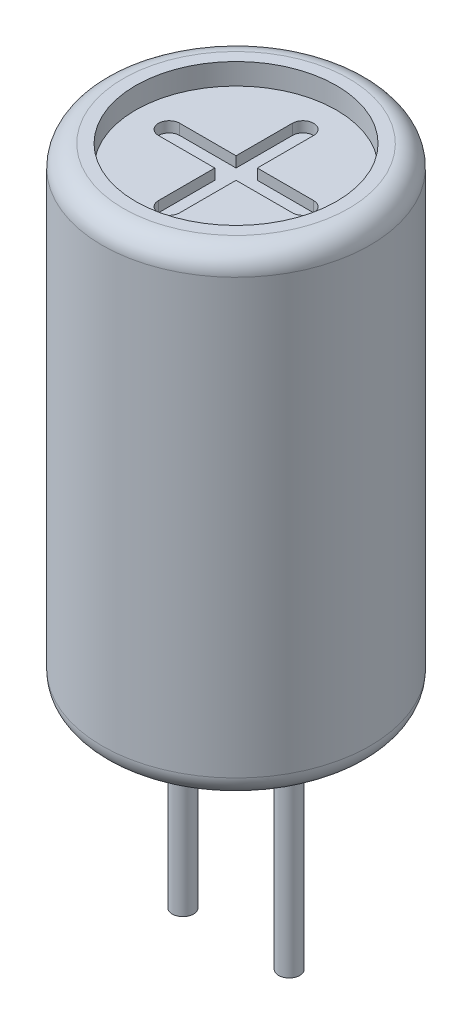
SolidWorks part; units mm, degrees
ref_plane "前视基准面" through (0, 0, 0) normal (0, 0, 1) x (1, 0, 0)
ref_plane "上视基准面" through (0, 0, 0) normal (0, 1, 0) x (1, 0, 0)
ref_plane "右视基准面" through (0, 0, 0) normal (1, 0, 0) x (0, 0, -1)
sketch "草图2" plane through (0, 0, 0) normal (0, 1, 0) x (1, 0, 0)
  circle A0 centre (0, 0) radius 3.15
  dimension "D1" = 6.3
extrude "凸台-拉伸1" add sketch "草图2" along normal blind 11.2 contours A0
fillet "圆角1" radius 0.5 2 edges at (0, 0, 3.15) (0, 11.2, 3.15)
sketch "草图3" plane through (0, 0, 0) normal (0, -1, 0) x (1, 0, 0)
  line L0 (-1.25, 0) -> (1.25, 0) construction
  circle A0 centre (-1.25, 0) radius 0.25
  circle A1 centre (1.25, 0) radius 0.25
  point P4 (0, 0)
  dimension "D2" = 0.5
  dimension "D3" = 0.5
  dimension "D1" = 2.5
extrude "凸台-拉伸2" add sketch "草图3" along normal blind 5
sketch "草图5" plane through (0, 11.2, 0) normal (0, 1, 0) x (1, 0, 0)
  circle A0 centre (0, 0) radius 2.3625
  dimension "D1" = 4.725
extrude "切除-拉伸1" cut sketch "草图5" against normal blind 1
sketch "草图6" plane through (0, 10.2, 0) normal (0, 1, 0) x (1, 0, 0)
  circle A0 centre (0, 0) radius 2.3625
extrude "凸台-拉伸3" add sketch "草图6" along normal blind 0.5
sketch "草图7" plane through (0, 10.7, 0) normal (0, 1, 0) x (1, 0, 0)
  line L0 (-1.575, 0) -> (1.575, 0) construction
  line L1 (-1.575, 0.25) -> (1.575, 0.25)
  line L2 (-1.575, -0.25) -> (1.575, -0.25)
  arc A0 (-1.575, 0.25) -> (-1.575, -0.25) centre (-1.575, 0) ccw
  arc A1 (1.575, -0.25) -> (1.575, 0.25) centre (1.575, 0) ccw
  point P2 (0, 0)
  dimension "D2" = 0.25
  dimension "D1" = 3.15
extrude "切除-拉伸2" cut sketch "草图7" against normal blind 0.25
sketch "草图8" plane through (0, 10.7, 0) normal (0, 1, 0) x (1, 0, 0)
  line L0 (0, -1.575) -> (0, 1.575) construction
  line L1 (-0.25, -1.575) -> (-0.25, 1.575)
  line L2 (0.25, -1.575) -> (0.25, 1.575)
  arc A0 (-0.25, -1.575) -> (0.25, -1.575) centre (0, -1.575) ccw
  arc A1 (0.25, 1.575) -> (-0.25, 1.575) centre (0, 1.575) ccw
  point P2 (0, 0)
  dimension "D2" = 0.25
  dimension "D1" = 3.15
extrude "切除-拉伸3" cut sketch "草图8" against normal blind 0.25
equation "\"R\"= 6.3'直径"
equation "\"D1@草图2\"=\"R\""
equation "\"H\"= 11.2'高度"
equation "\"M\"= 2.5'引脚间距"
equation "\"P\"= 0.5'引脚直径"
equation "\"D1@凸台-拉伸1\"=\"H\""
equation "\"D2@草图3\"=\"P\""
equation "\"D3@草图3\"=\"P\""
equation "\"D1@草图3\"=\"M\""
equation "\"L\"= 5'引脚长度"
equation "\"D1@凸台-拉伸2\"=\"L\""
equation "\"D1@草图5\"=\"R\"*3/4"
equation "\"D1@草图7\"=\"R\"/2"
equation "\"D1@草图8\"=\"R\"/2"
